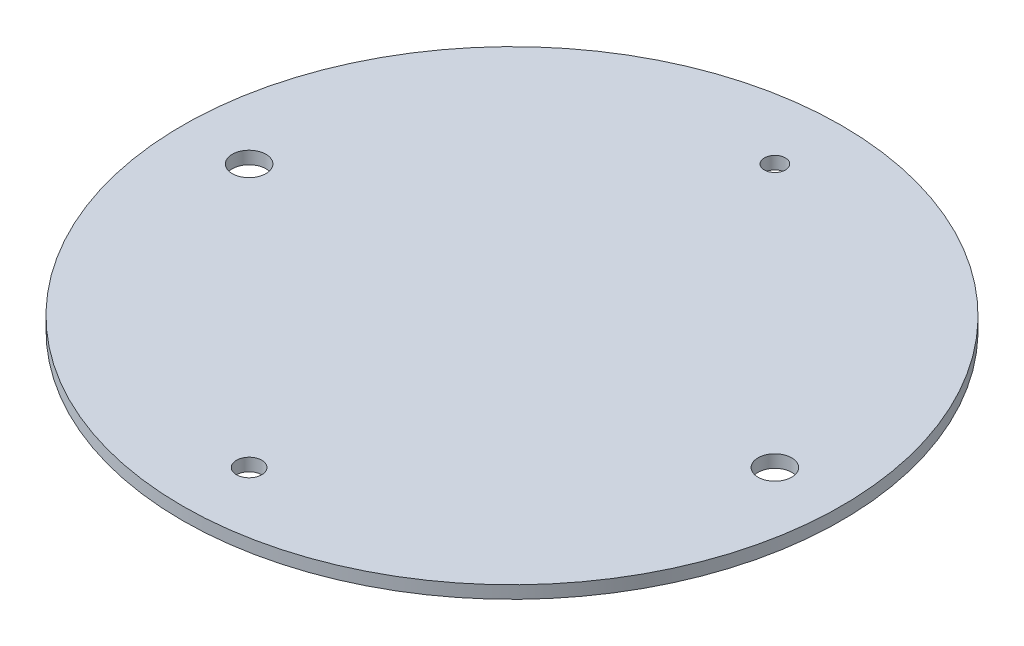
SolidWorks part; units mm, degrees
material "1060 Alloy"
ref_plane "Front Plane" through (0, 0, 0) normal (0, 0, 1) x (1, 0, 0)
ref_plane "Top Plane" through (0, 0, 0) normal (0, 1, 0) x (1, 0, 0)
ref_plane "Right Plane" through (0, 0, 0) normal (1, 0, 0) x (0, 0, -1)
sketch "Sketch1" plane through (0, 0, 0) normal (0, 1, 0) x (1, 0, 0)
  circle A0 centre (0, 0) radius 78.35
  circle A1 centre (-62.5, 0) radius 4
  circle A2 centre (0, 0) radius 62.5 construction
  circle A3 centre (0, -62.5) radius 3
  circle A4 centre (0, 62.5) radius 2.5
  circle A5 centre (62.5, 0) radius 4
  dimension "D1" = 156.7
  dimension "D2" = 125
  dimension "D3" = 8
  dimension "D4" = 8
  dimension "D5" = 5
  dimension "D6" = 6
extrude "Boss-Extrude1" add sketch "Sketch1" along normal blind 3
